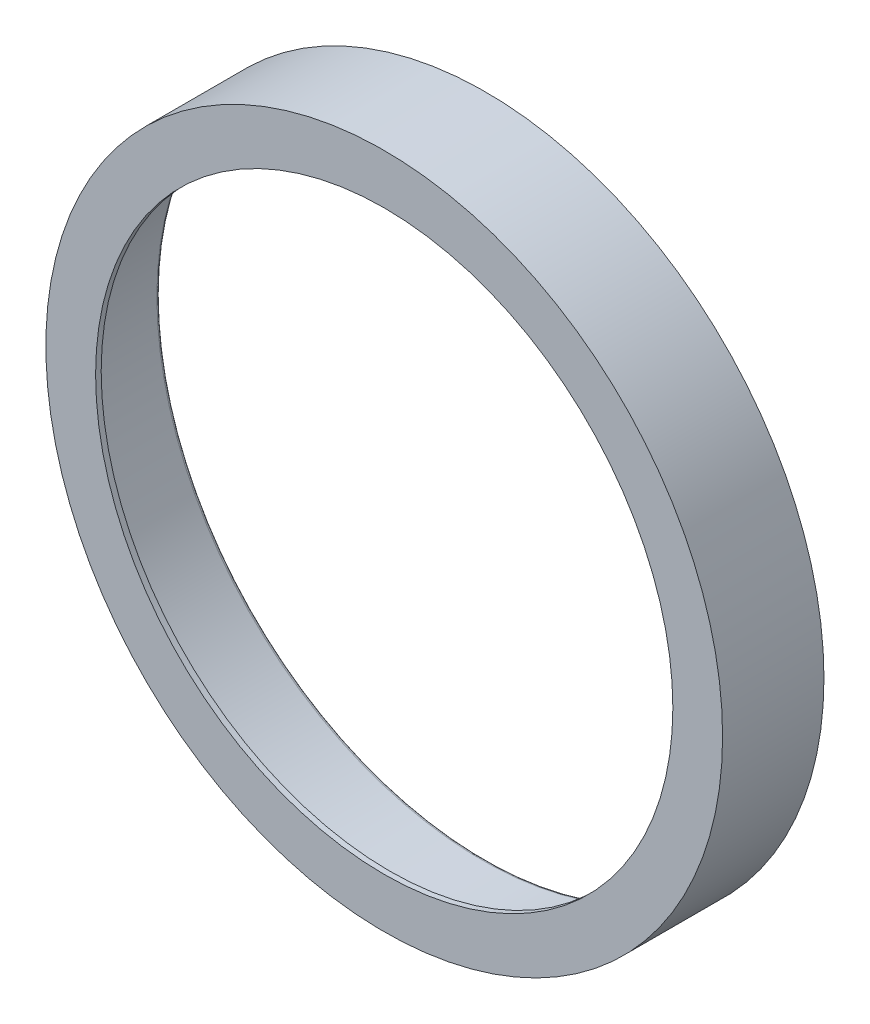
SolidWorks part; units mm, degrees
ref_plane "Front Plane" through (0, 0, 0) normal (0, 0, 1) x (1, 0, 0)
ref_plane "Top Plane" through (0, 0, 0) normal (0, 1, 0) x (1, 0, 0)
ref_plane "Right Plane" through (0, 0, 0) normal (1, 0, 0) x (0, 0, -1)
sketch "Baseplate" plane through (0, 0, 0) normal (0, 0, 1) x (1, 0, 0)
  circle A0 centre (0, 0) radius 106
  circle A1 centre (0, 0) radius 90.4143
  point P5 (-365.615, -71.242)
extrude "Boss-Extrude1" add sketch "Baseplate" along normal blind 31.75
sketch "Sketch2" plane through (0, 0, 0) normal (0, 0, -1) x (-1, 0, 0)
  circle A0 centre (0, 0) radius 101.972
extrude "Cut-Extrude1" cut sketch "Sketch2" against normal blind 30
fillet "Fillet1" radius 1 1 edges at (-101.972, 0, 0)
fillet "Fillet2" radius 1 1 edges at (-101.972, 0, 30)
